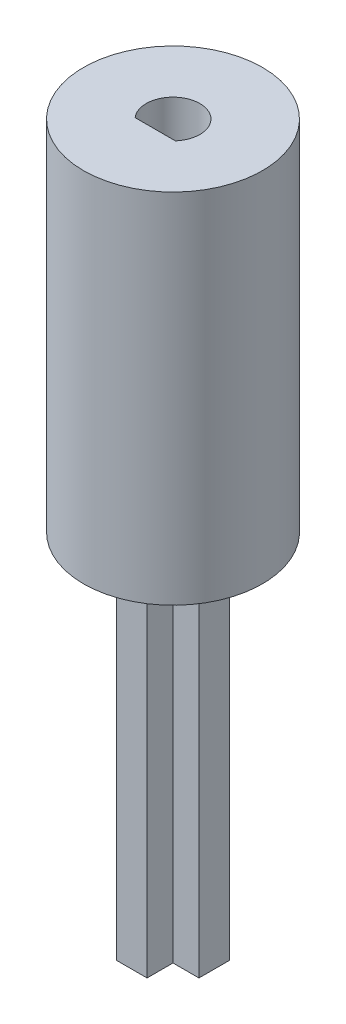
SolidWorks part; units mm, degrees
ref_plane "Front Plane" through (0, 0, 0) normal (0, 0, 1) x (1, 0, 0)
ref_plane "Top Plane" through (0, 0, 0) normal (0, 1, 0) x (1, 0, 0)
ref_plane "Right Plane" through (0, 0, 0) normal (1, 0, 0) x (0, 0, -1)
sketch "Sketch2" plane through (0, 0, 0) normal (0, 1, 0) x (1, 0, 0)
  line L6 (-0.85, 2.3) -> (0.85, 2.3)
  line L11 (-0.85, 2.3) -> (-0.85, 0.85)
  line L12 (-0.85, -2.3) -> (0.85, -2.3)
  line L13 (0.85, 2.3) -> (0.85, 0.85)
  line L19 (-2.3, 0.85) -> (-0.85, 0.85)
  line L20 (-2.3, 0.85) -> (-2.3, -0.85)
  line L21 (-2.3, -0.85) -> (-0.85, -0.85)
  line L22 (2.3, 0.85) -> (2.3, -0.85)
  line L26 (-0.85, -0.85) -> (-0.85, -2.3)
  line L29 (0.85, -0.85) -> (0.85, -2.3)
  line L31 (0.85, 0.85) -> (2.3, 0.85)
  line L32 (0.85, -0.85) -> (2.3, -0.85)
  point P0 (0, 0)
  point P6 (0, 0)
  dimension "D1" = 1.7
  dimension "D2" = 1.7
  dimension "D3" = 4.6
  dimension "D4" = 4.6
extrude "Boss-Extrude1" add sketch "Sketch2" along normal blind 20
sketch "Sketch3" plane through (0, 20, 0) normal (0, 1, 0) x (1, 0, 0)
  circle A0 centre (0, 0) radius 5
  dimension "D1" = 10
extrude "Boss-Extrude2" add sketch "Sketch3" along normal blind 20
sketch "Sketch4" plane through (0, 40, 0) normal (0, 1, 0) x (1, 0, 0)
  line L0 (0, 0) -> (0, -0.9922) construction
  line L2 (-1.125, -0.9922) -> (1.125, -0.9922)
  arc A1 (1.125, -0.9922) -> (-1.125, -0.9922) centre (0, 0) ccw
  dimension "D1" = 3
  dimension "D2" = 2.25
extrude "Cut-Extrude1" cut sketch "Sketch4" against normal blind 10
